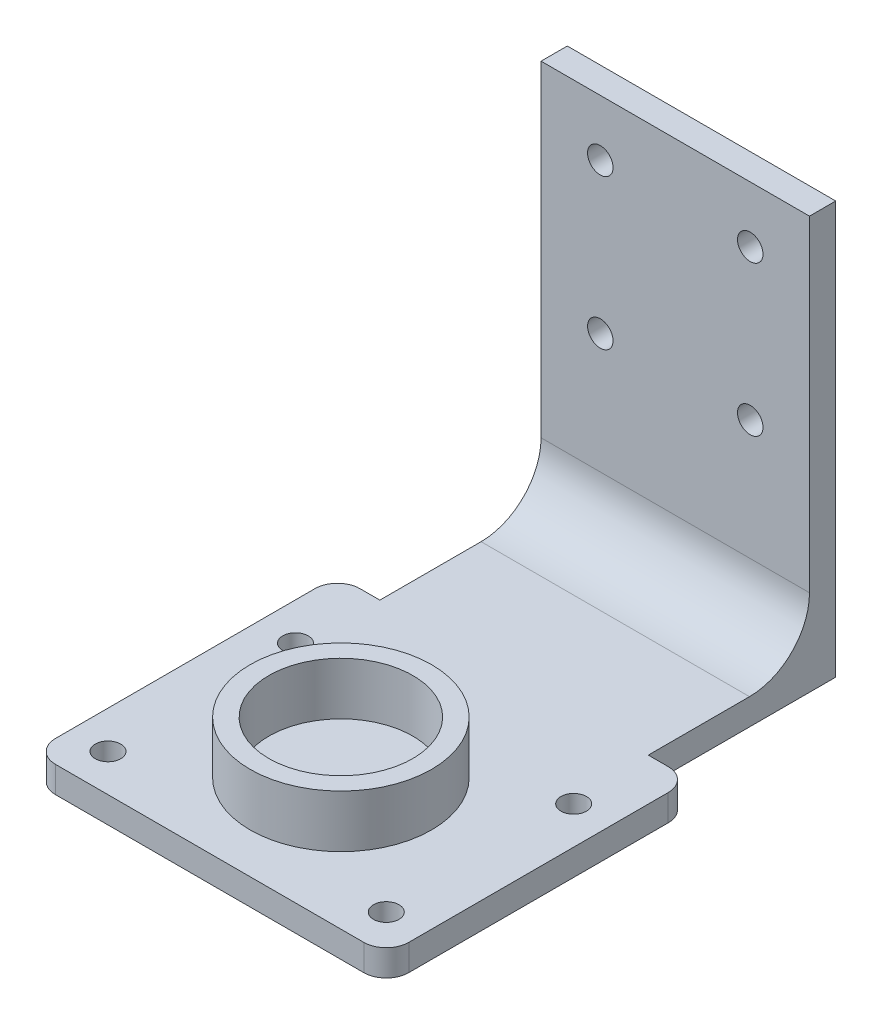
SolidWorks part; units mm, degrees
ref_plane "Front Plane" through (0, 0, 0) normal (0, 0, 1) x (1, 0, 0)
ref_plane "Top Plane" through (0, 0, 0) normal (0, 1, 0) x (1, 0, 0)
ref_plane "Right Plane" through (0, 0, 0) normal (1, 0, 0) x (0, 0, -1)
sketch "Sketch1" plane through (0, 0, 0) normal (0, 1, 0) x (1, 0, 0)
  line L0 (0, 0) -> (0, 44.6) construction
  line L1 (-23.555, 17.5) -> (23.555, 17.5) construction
  line L2 (-23.555, 17.5) -> (-23.555, -17.5)
  line L3 (-23.555, -17.5) -> (23.555, -17.5)
  line L4 (23.555, 17.5) -> (23.555, -17.5)
  line L5 (0, -17.5) -> (0, 17.5) construction
  line L6 (-23.555, 0) -> (23.555, 0) construction
  line L7 (-23.555, 17.5) -> (-23.555, 44.6)
  line L8 (-23.555, 44.6) -> (23.555, 44.6)
  line L9 (23.555, 44.6) -> (23.555, 17.5)
  circle A0 centre (-18.555, -12.5) radius 1.7
  circle A1 centre (-18.555, 12.5) radius 1.7
  circle A2 centre (18.555, -12.5) radius 1.7
  circle A3 centre (18.555, 12.5) radius 1.7
  point P224 (0, 0)
  dimension "D3" = 3.4
  dimension "D1" = 47.11
  dimension "D2" = 35
  dimension "D4" = 5
  dimension "D5" = 5
  dimension "D6" = 44.6
extrude "Boss-Extrude1" add sketch "Sketch1" along normal blind 3.5
sketch "Sketch2" plane through (0, 3.5, 0) normal (0, 1, 0) x (1, 0, 0)
  circle A0 centre (0, 0) radius 9.6
  circle A1 centre (0, 0) radius 12.1
  dimension "D1" = 19.2
  dimension "D2" = 2.5
extrude "Boss-Extrude2" add sketch "Sketch2" along normal blind 7
sketch "Sketch3" plane through (0, 0, -44.6) normal (0, 0, -1) x (-1, 0, 0)
  line L0 (-23.555, 0) -> (-23.555, 55)
  line L1 (-23.555, 55) -> (23.555, 55)
  line L2 (23.555, 55) -> (23.555, 0)
  line L3 (23.555, 0) -> (-23.555, 0)
  dimension "D1" = 55
extrude "Boss-Extrude3" add sketch "Sketch3" along normal blind 3.5
sketch "Sketch4" plane through (0, 0, -48.1) normal (0, 0, -1) x (-1, 0, 0)
  line L1 (-10, 47.5) -> (10, 47.5) construction
  line L2 (-10, 47.5) -> (-10, 27.5) construction
  line L3 (-10, 27.5) -> (10, 27.5) construction
  line L4 (10, 47.5) -> (10, 27.5) construction
  line L5 (0, 27.5) -> (0, 47.5) construction
  line L6 (-10, 37.5) -> (10, 37.5) construction
  line L7 (-23.555, 0) -> (23.555, 0) construction
  circle A0 centre (-10, 47.5) radius 1.7
  circle A1 centre (-10, 27.5) radius 1.7
  circle A2 centre (10, 27.5) radius 1.7
  circle A3 centre (10, 47.5) radius 1.7
  point P4 (10.3642, 31.8741)
  point P10 (10, 31.4609)
  point P11 (-9.5581, 11.8741)
  point P13 (0, 0)
  point P15 (10, 11.4811)
  point P172 (0, 37.5)
  dimension "D3" = 3.4
  dimension "D1" = 20
  dimension "D2" = 20
  dimension "D4" = 37.5
extrude "Cut-Extrude1" cut sketch "Sketch4" against normal through all
sketch "Sketch5" plane through (0, 55, 0) normal (0, 1, 0) x (1, 0, 0)
  line L0 (-23.555, 48.1) -> (-23.555, 23.1)
  line L1 (-23.555, 44.6) -> (-23.555, -17.5) construction
  line L2 (-23.555, 23.1) -> (-17.9, 23.1)
  line L3 (-17.9, 23.1) -> (-17.9, 48.1)
  line L4 (-23.555, 48.1) -> (23.555, 48.1) construction
  line L5 (-17.9, 48.1) -> (-23.555, 48.1)
  line L6 (0, 48.1) -> (0, -17.5) construction
  line L7 (-23.555, -17.5) -> (23.555, -17.5) construction
  line L8 (23.555, 48.1) -> (23.555, 23.1)
  line L9 (17.9, 48.1) -> (23.555, 48.1)
  line L10 (17.9, 23.1) -> (17.9, 48.1)
  line L11 (23.555, 23.1) -> (17.9, 23.1)
  dimension "D1" = 25
  dimension "D2" = 35.8
extrude "Cut-Extrude2" cut sketch "Sketch5" against normal through all
fillet "Fillet3" radius 3 4 edges at (23.555, 1.75, -23.1) (23.555, 1.75, 17.5) (-23.555, 1.75, -23.1) (-23.555, 1.75, 17.5)
fillet "Fillet4" radius 8 1 edges at (0, 3.5, -44.6)
